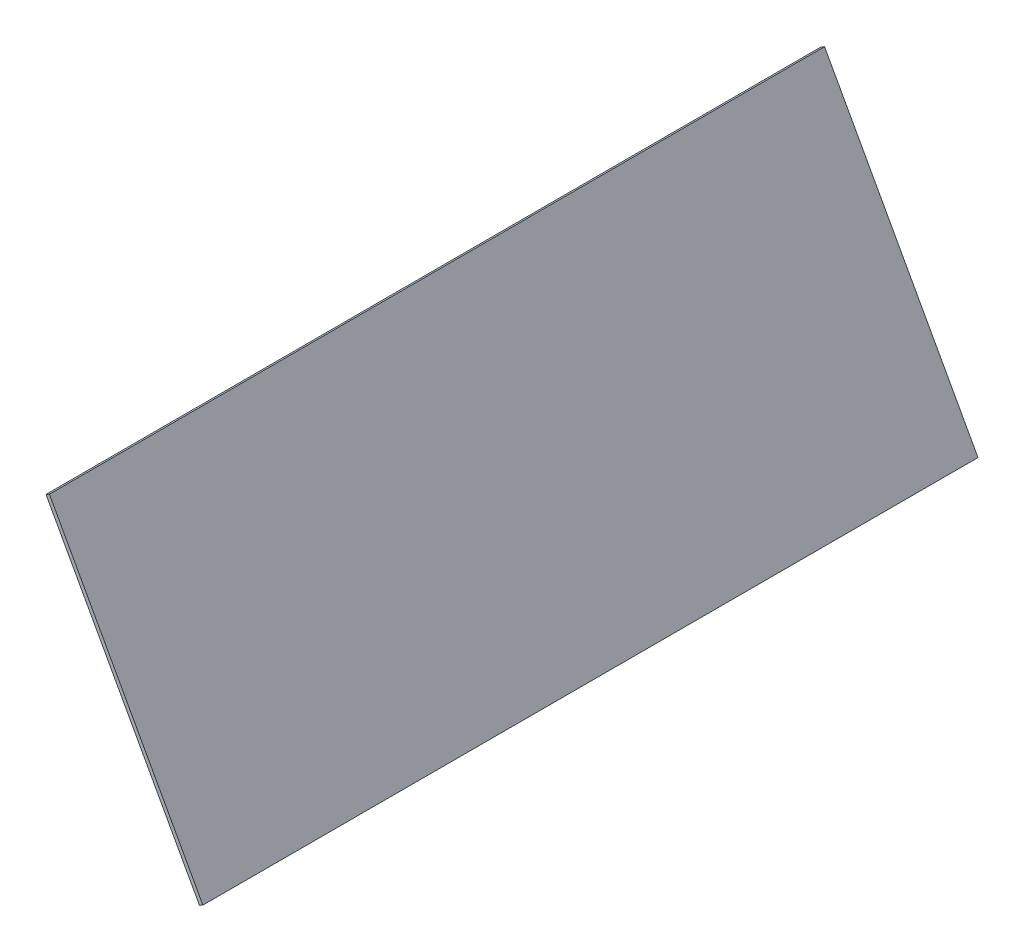
SolidWorks part; units mm, degrees
ref_plane "Front Plane" through (0, 0, 0) normal (0, 0, 1) x (1, 0, 0)
ref_plane "Top Plane" through (0, 0, 0) normal (0, 1, 0) x (1, 0, 0)
ref_plane "Right Plane" through (0, 0, 0) normal (1, 0, 0) x (0, 0, -1)
sketch "Sloping front closure profile" plane through (0, 0, 0) normal (0, 0, 1) x (1, 0, 0)
  line L0 (54, 107) -> (54.87, 107.48)
  line L1 (54.87, 107.48) -> (94.07, 36.18)
  line L2 (94.07, 36.18) -> (93.2, 35.7)
  line L3 (93.2, 35.7) -> (54, 107)
extrude "Sloping front closure" add sketch "Sloping front closure profile" along normal blind 198
